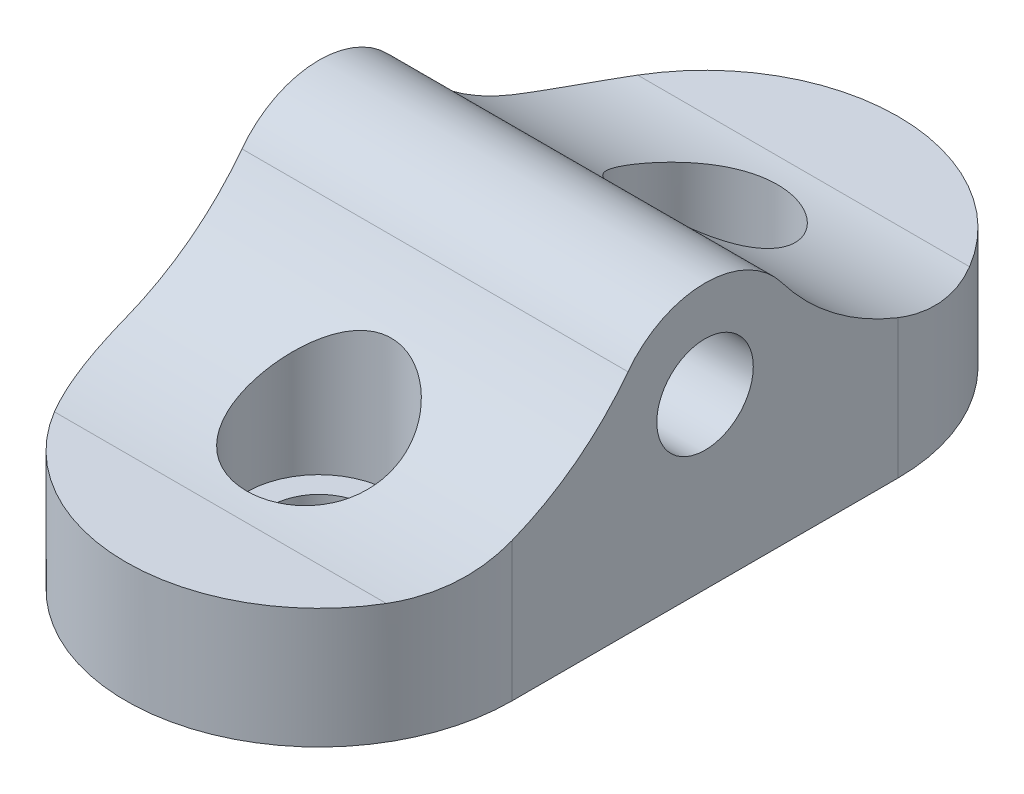
SolidWorks part; units mm, degrees
material "6061-T6 (SS)"
ref_plane "Front Plane" through (0, 0, 0) normal (0, 0, 1) x (1, 0, 0)
ref_plane "Top Plane" through (0, 0, 0) normal (0, 1, 0) x (1, 0, 0)
ref_plane "Right Plane" through (0, 0, 0) normal (1, 0, 0) x (0, 0, -1)
sketch "Sketch2" plane through (0, 0, 0) normal (0, 1, 0) x (1, 0, 0)
  line L0 (0, 12.7) -> (0, -12.7) construction
  line L1 (12.7, 12.7) -> (12.7, -12.7)
  line L2 (-12.7, 12.7) -> (-12.7, -12.7)
  arc A0 (12.7, 12.7) -> (-12.7, 12.7) centre (0, 12.7) ccw
  arc A1 (-12.7, -12.7) -> (12.7, -12.7) centre (0, -12.7) ccw
  circle A2 centre (0, 12.7) radius 3.175
  circle A3 centre (0, -12.7) radius 3.175
  point P3 (0, 0)
  dimension "D1" = 12.7
  dimension "D3" = 6.35
  dimension "D2" = 25.4
extrude "Boss-Extrude1" add sketch "Sketch2" along normal blind 25.4
sketch "Sketch3" plane through (0, 0, 0) normal (1, 0, 0) x (0, 0, -1)
  line L0 (-25.4, 7.9058) -> (-19.1866, 7.9058)
  line L1 (-25.4, 25.4) -> (-25.4, 0) construction
  line L2 (19.1866, 7.9058) -> (25.4, 7.9058)
  line L3 (25.4, 0) -> (25.4, 25.4) construction
  line L4 (-25.4, 7.9058) -> (-31.2072, 35.2011)
  line L5 (-31.2072, 35.2011) -> (25.4, 30.0156)
  line L6 (25.4, 30.0156) -> (25.4, 7.9058)
  line L7 (12.7, 0) -> (25.4, 0) construction
  circle A0 centre (0, 11.1125) radius 11.1125 construction
  circle A1 centre (0, 11.1125) radius 3.175
  arc A2 (-19.1866, 7.9058) -> (-5.0684, 14.938) centre (-19.1866, 25.5941) ccw
  arc A3 (-5.0684, 14.938) -> (5.0684, 14.938) centre (0, 11.1125) cw
  arc A4 (5.0684, 14.938) -> (19.1866, 7.9058) centre (19.1866, 25.5941) ccw
  dimension "D1" = 22.225
  dimension "D2" = 6.35
  dimension "D3" = 6.35
  dimension "D4" = 7.9058
extrude "Cut-Extrude1" cut sketch "Sketch3" against normal through all both and the other way through all
ref_plane "Plane1" through (0, 25.4, 0) normal (0, 1, 0) x (1, 0, 0)
sketch "Sketch4" plane through (0, 25.4, 0) normal (0, 1, 0) x (1, 0, 0)
  circle A0 centre (0, -12.7) radius 4.7625
  circle A1 centre (0, 12.7) radius 4.7625
  dimension "D1" = 9.525
extrude "Cut-Extrude2" cut sketch "Sketch4" against normal offset from surface (22.225 mm away) 3.175 up to face at (0, 0, 0)
